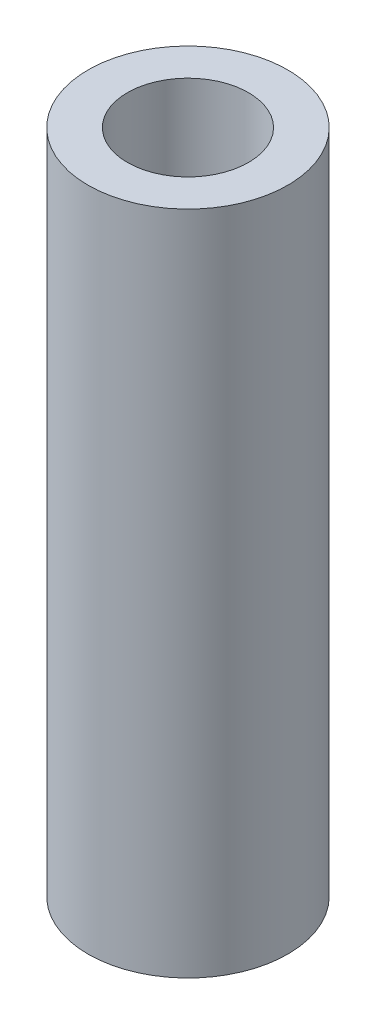
SolidWorks part; units mm, degrees
ref_plane "前视基准面" through (0, 0, 0) normal (0, 0, 1) x (1, 0, 0)
ref_plane "上视基准面" through (0, 0, 0) normal (0, 1, 0) x (1, 0, 0)
ref_plane "右视基准面" through (0, 0, 0) normal (1, 0, 0) x (0, 0, -1)
sketch "M2铜柱草图" plane through (0, 0, 0) normal (0, 1, 0) x (1, 0, 0)
  circle A0 centre (0, 0) radius 1
  circle A1 centre (0, 0) radius 1.65
extrude "M2铜柱" add sketch "M2铜柱草图" along normal blind 11
